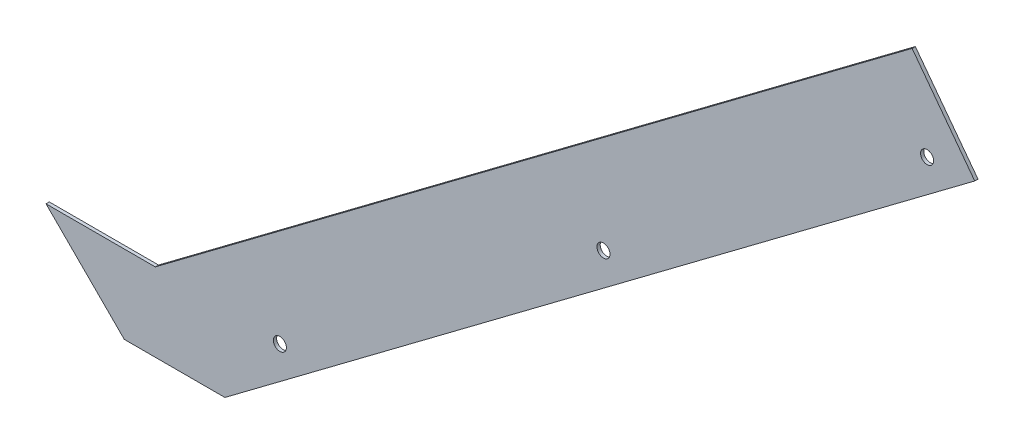
SolidWorks part; units mm, degrees
material "Magnesium Alloy"
ref_plane "Front Plane" through (0, 0, 0) normal (0, 0, 1) x (1, 0, 0)
ref_plane "Top Plane" through (0, 0, 0) normal (0, 1, 0) x (1, 0, 0)
ref_plane "Right Plane" through (0, 0, 0) normal (1, 0, 0) x (0, 0, -1)
sketch "Sketch1" plane through (0, 0, 0) normal (0, 0, 1) x (1, 0, 0)
  line L0 (0, 0) -> (53.1812, 0)
  line L1 (53.1812, 0) -> (421.4812, 276.225)
  line L2 (421.4812, 276.225) -> (451.9613, 235.585)
  line L4 (38.1, -38.1) -> (0, 0)
  line L5 (451.9613, 235.585) -> (87.0479, -38.1)
  line L6 (87.0479, -38.1) -> (38.1, -38.1)
  dimension "D1" = 53.1812
  dimension "D2" = 460.375
  dimension "D3" = 38.1
  dimension "D4" = 38.1
  dimension "D5" = 50.8
  dimension "D6" = 368.3
extrude "Boss-Extrude1" add sketch "Sketch1" along normal blind 1.5875
hole_wizard "1/4 (0.25) Diameter Hole1" positions "Sketch2" profile "Sketch3" hole size "1/4" standard "ANSI Inch" end condition through all
sketch "Sketch2" plane through (0, 0, 1.5875) normal (0, 0, 1) x (1, 0, 0)
  line L0 (421.4812, 276.225) -> (53.1812, 0) construction
  line L1 (451.9613, 235.585) -> (421.4812, 276.225) construction
  point P0 (428.771, 234.0673)
  point P2 (271.291, 115.9573)
  point P4 (113.811, -2.1527)
  dimension "D1" = 38.1
  dimension "D2" = 19.4629
  dimension "D3" = 216.3129
  dimension "D4" = 38.1
  dimension "D5" = 413.1629
  dimension "D6" = 38.1
sketch "Sketch3" plane through (428.771, 234.0673, 1.5875) normal (1, 0, 0) x (0, -1, 0)
  line L0 (0, 0) -> (0, 1.5875)
  line L1 (0, 1.5875) -> (3.175, 1.5875)
  line L2 (3.175, 1.5875) -> (3.175, 0)
  line L5 (3.175, 0) -> (0, 0)
  line L11 (0, -6.35) -> (0, 107.95) construction
  dimension "Thru Hole Dia." = 6.35
  dimension "Thru Hole Depth" = 1.5875
